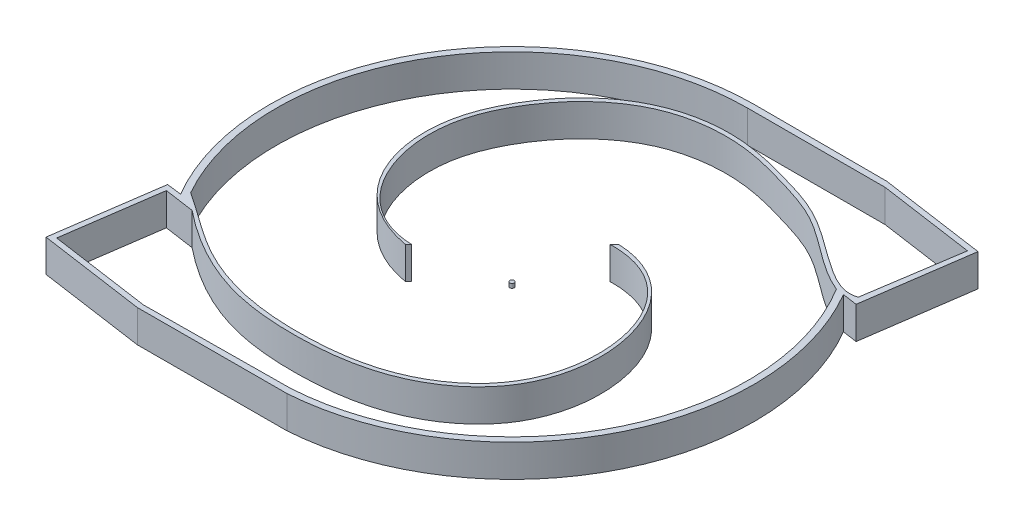
SolidWorks part; units mm, degrees
material "ABS"
ref_plane "Alzado" through (0, 0, 0) normal (0, 0, 1) x (1, 0, 0)
ref_plane "Planta" through (0, 0, 0) normal (0, 1, 0) x (1, 0, 0)
ref_plane "Vista lateral" through (0, 0, 0) normal (1, 0, 0) x (0, 0, -1)
sketch "Croquis1" plane through (0, 0, 0) normal (0, 1, 0) x (1, 0, 0)
  line L0 (0.2162, 112.4998) -> (61.6062, 112.3818)
  line L1 (-120, 120) -> (120, 120) construction
  line L2 (-120, 120) -> (-120, -120) construction
  line L3 (-120, -120) -> (120, -120) construction
  line L4 (120, 120) -> (120, -120) construction
  line L5 (-120, 120) -> (120, -120) construction
  line L6 (-120, -120) -> (120, 120) construction
  line L10 (-0.0888, 109.5) -> (24.7487, 109.5201)
  line L11 (63.7253, 109.5517) -> (108.357, 103.1402)
  line L13 (108.357, 103.1402) -> (101.6511, 59.2211)
  line L15 (-61.6062, -112.3818) -> (7.8133, -112.2283)
  line L21 (-61.2507, -109.9072) -> (6.5286, -109.3052)
  line L22 (-23.3345, -23.3345) -> (-24.7487, -24.7487)
  line L23 (22.7487, 22.7487) -> (24.7487, 24.7487)
  line L25 (-61.6062, -112.3818) -> (-54.4964, -62.8899) construction
  line L26 (103.9884, 55.7801) -> (97.1284, 56.7656)
  line L27 (61.6062, 112.3818) -> (111.0981, 105.2721)
  line L28 (111.0981, 105.2721) -> (103.9884, 55.7801)
  line L30 (-101.8692, -58.6102) -> (-108.268, -103.1529) construction
  line L31 (-97.1284, -56.7656) -> (-104.0054, -55.899)
  line L32 (-104.0054, -55.899) -> (-111.0981, -105.2721)
  line L34 (-108.268, -103.1529) -> (-101.8692, -58.6102)
  line L35 (-101.8692, -58.6102) -> (-87.9164, -60.6146)
  line L36 (-108.268, -103.1529) -> (-63.7253, -109.5517) construction
  line L37 (-57.3265, -65.009) -> (-101.8692, -58.6102) construction
  line L38 (-103.9884, -55.7801) -> (-111.0981, -105.2721) construction
  line L43 (24.7487, 109.5201) -> (63.7253, 109.5517)
  line L44 (-111.0981, -105.2721) -> (-61.6062, -112.3818)
  line L45 (-61.2507, -109.9072) -> (-108.268, -103.1529)
  circle A0 centre (0, 0) radius 112.5 construction
  arc A1 (0.2162, 112.4998) -> (-97.1284, -56.7656) centre (0, 0) ccw
  arc A2 (-0.0888, 109.5) -> (-95.3218, -53.8887) centre (0, 0) ccw
  arc A3 (7.8133, -112.2283) -> (97.1284, 56.7656) centre (0, 0) ccw
  arc A4 (6.5286, -109.3052) -> (93.3017, 57.3153) centre (0, 0) ccw
  spline S0 degree 3 poles (101.6511, 59.2211) (91.0384, 54.8394) (67.3504, 81.8497) (38.8537, 89.1413) (40.3725, 88.6774) (10.8987, 98.1526) (-30.7206, 90.5568) (-54.9323, 63.3856) (-72.3021, 19.825) (-57.6089, -18.8674) (-24.7487, -24.7487) knots 0 0 0 0 0.180134 0.261356 0.280027 0.366845 0.472528 0.63773 0.722543 1 1 1 1
  spline S1 degree 3 poles (24.7487, 24.7487) (51.7371, 23.6622) (72.1161, -11.817) (59.7863, -59.0149) (28.209, -83.0353) (-9.8226, -88.3388) (-51.5864, -84.7534) (-75.9728, -70.2919) (-87.9164, -60.6146) knots 0 0 0 0 0.260568 0.392123 0.526871 0.686922 0.822472 1 1 1 1
  spline S2 degree 3 poles (-23.3345, -23.3345) (-53.1429, -22.1928) (-70.9286, 17.7733) (-52.9708, 63.4031) (-26.3511, 90.7646) (11.7545, 95.0233) (37.4033, 87.7996) (65.3229, 78.7682) (79.9999, 62.7849) (93.3017, 57.3153) knots 0 0 0 0 0.284776 0.367115 0.543283 0.675927 0.771894 0.839957 1 1 1 1
  spline S3 degree 3 poles (22.7487, 22.7487) (50.5691, 23.4959) (70.0832, -11.1972) (58.3489, -57.6594) (27.696, -80.9952) (-9.7638, -86.3617) (-42.2901, -83.5973) (-71.2177, -72.0334) (-85.5952, -60.1599) (-95.3218, -53.8887) knots 0 0 0 0 0.24925 0.376492 0.507985 0.654062 0.793176 0.869807 1 1 1 1
  point P0 (0, 0)
  dimension "D3" = 225
  dimension "D4" = 3
  dimension "D5" = 2
  dimension "D1" = 240
  dimension "D2" = 240
  dimension "D6" = 2
  dimension "D11" = 35
  dimension "D12" = 35
  dimension "D13" = 80
  dimension "D14" = 80
  dimension "D15" = 2
  dimension "D16" = 2
  dimension "D17" = 2
  dimension "D18" = 2
  dimension "D19" = 2
  dimension "D20" = 2
  dimension "D21" = 2
  dimension "D22" = 2
  dimension "D23" = 2
  dimension "D24" = 2
  dimension "D25" = 2
  dimension "D26" = 2
  dimension "D27" = 2
  dimension "D28" = 2
  dimension "D29" = 2
extrude "Saliente-Extruir1" add sketch "Croquis1" along normal blind 15
sketch "Croquis2" plane through (0, 0, 0) normal (0, -1, 0) x (1, 0, 0)
  circle A1 centre (0, 0) radius 1
  dimension "D1" = 2
extrude "Saliente-Extruir2" add sketch "Croquis2" along normal blind 2 separate body
